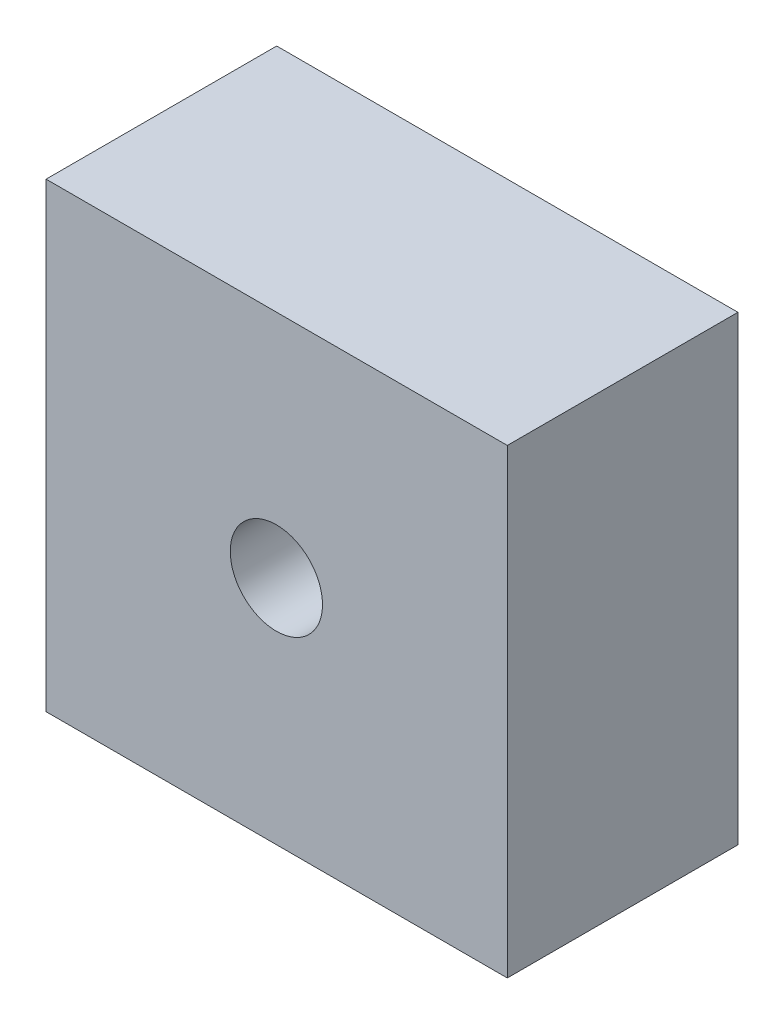
SolidWorks part; units mm, degrees
ref_plane "前视基准面" through (0, 0, 0) normal (0, 0, 1) x (1, 0, 0)
ref_plane "上视基准面" through (0, 0, 0) normal (0, 1, 0) x (1, 0, 0)
ref_plane "右视基准面" through (0, 0, 0) normal (1, 0, 0) x (0, 0, -1)
other "Configuration Table"
sketch "草图1" plane through (0, 0, 0) normal (0, 0, 1) x (1, 0, 0)
  line L1 (0, 0) -> (20, 0)
  line L2 (0, 0) -> (0, 20)
  line L3 (0, 20) -> (20, 20)
  line L4 (20, 0) -> (20, 20)
extrude "BaseBox" add sketch "草图1" along normal blind 10
hole_wizard "孔1" positions "草图3" profile "草图2" legacy
sketch "草图3" plane through (0, 0, 10) normal (0, 0, 1) x (1, 0, 0)
  point P0 (9.9865, 10.0143)
sketch "草图2" plane through (9.9865, 10.0143, 10) normal (1, 0, 0) x (0, -1, 0)
  line L0 (0, 0) -> (0, 10)
  line L1 (0, 10) -> (2, 10)
  line L2 (2, 10) -> (2, 0)
  line L3 (2, 0) -> (0, 0)
  line L4 (0, 110) -> (0, -10) construction
  dimension "直径" = 4
  dimension "深度" = 10
